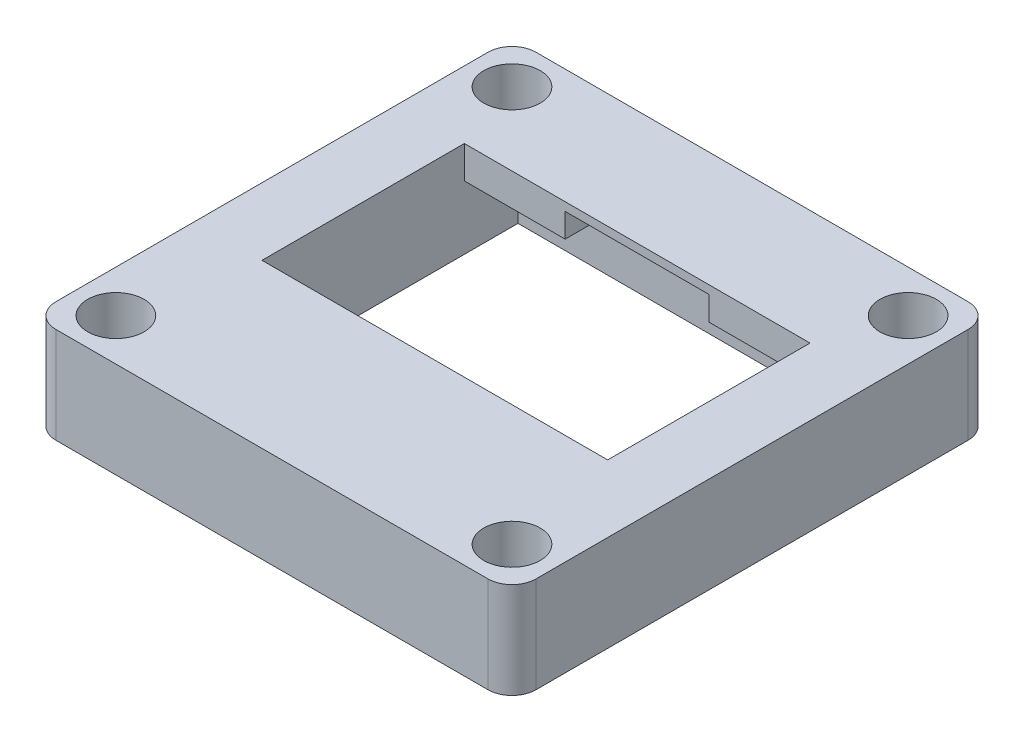
SolidWorks part; units mm, degrees
ref_plane "Спереди" through (0, 0, 0) normal (0, 0, 1) x (1, 0, 0)
ref_plane "Сверху" through (0, 0, 0) normal (0, 1, 0) x (1, 0, 0)
ref_plane "Справа" through (0, 0, 0) normal (1, 0, 0) x (0, 0, -1)
sketch "габариты дисплея" plane through (0, 0, 0) normal (0, 1, 0) x (1, 0, 0)
  line L1 (-13.6, -13.6) -> (13.6, -13.6)
  line L2 (-13.6, -13.6) -> (-13.6, 13.6)
  line L3 (-13.6, 13.6) -> (13.6, 13.6)
  line L4 (13.6, -13.6) -> (13.6, 13.6)
  line L5 (-13.6, -13.6) -> (13.6, 13.6) construction
  line L6 (-13.6, 13.6) -> (13.6, -13.6) construction
  line L7 (-13.6, -9.63) -> (13.6, -9.63)
  line L8 (-13.6, -9.63) -> (-13.6, 9.63)
  line L9 (-13.6, 9.63) -> (13.6, 9.63)
  line L10 (13.6, -9.63) -> (13.6, 9.63)
  line L11 (-13.6, -9.63) -> (13.6, 9.63) construction
  line L12 (-13.6, 9.63) -> (13.6, -9.63) construction
  line L13 (-11.6, -11.6) -> (11.6, -11.6) construction
  line L14 (-11.6, -11.6) -> (-11.6, 11.6) construction
  line L15 (-11.6, 11.6) -> (11.6, 11.6) construction
  line L16 (11.6, -11.6) -> (11.6, 11.6) construction
  line L17 (-11.6, -11.6) -> (11.6, 11.6) construction
  line L18 (-11.6, 11.6) -> (11.6, -11.6) construction
  circle A0 centre (-11.6, 11.6) radius 1.25
  circle A1 centre (11.6, 11.6) radius 1.25
  circle A2 centre (11.6, -11.6) radius 1.25
  circle A3 centre (-11.6, -11.6) radius 1.25
  point P0 (0, 0)
  point P6 (0, 0)
  point P12 (0, 0)
  dimension "D5" = 2.5
  dimension "D1" = 19.26
  dimension "D2" = 27.2
  dimension "D3" = 27.2
  dimension "D4" = 2
sketch "Эскиз1" plane through (0, 0, 0) normal (0, 1, 0) x (1, 0, 0)
  line L1 (-20, 20) -> (20, 20)
  line L2 (-20, 20) -> (-20, -20)
  line L3 (-20, -20) -> (20, -20)
  line L4 (20, 20) -> (20, -20)
  line L5 (-20, 20) -> (20, -20) construction
  line L6 (-20, -20) -> (20, 20) construction
  point P0 (0, 0)
  dimension "D1" = 40
  dimension "D2" = 40
extrude "тело" add sketch "Эскиз1" along normal blind 8
sketch "Эскиз2" plane through (0, 0, 0) normal (0, -1, 0) x (1, 0, 0)
  line L0 (-13.6, 13.6) -> (13.6, 13.6) construction
  line L1 (-14.4, -14.9) -> (14.4, -14.9)
  line L2 (-14.4, -14.9) -> (-14.4, 14.9)
  line L3 (-14.4, 14.9) -> (14.4, 14.9)
  line L4 (14.4, -14.9) -> (14.4, 14.9)
  line L5 (-14.4, -14.9) -> (14.4, 14.9) construction
  line L6 (-14.4, 14.9) -> (14.4, -14.9) construction
  line L7 (13.6, 13.6) -> (13.6, -13.6) construction
  point P0 (0, 0)
  dimension "D1" = 1.3
  dimension "D2" = 0.8
extrude "углубление для платы" cut sketch "Эскиз2" against normal offset from surface (5.3 mm away) 2.7 up to face at (0, 8, 0)
sketch "Эскиз3" plane through (0, 5.3, 0) normal (0, -1, 0) x (1, 0, 0)
  line L0 (14.4, -14.9) -> (14.4, 14.9) construction
  line L1 (-14.4, -10.43) -> (14.4, -10.43)
  line L2 (-14.4, -10.43) -> (-14.4, 10.43)
  line L3 (-14.4, 10.43) -> (14.4, 10.43)
  line L4 (14.4, -10.43) -> (14.4, 10.43)
  line L5 (-14.4, -10.43) -> (14.4, 10.43) construction
  line L6 (-14.4, 10.43) -> (14.4, -10.43) construction
  line L7 (-13.6, 9.63) -> (13.6, 9.63) construction
  point P0 (0, 0)
  dimension "D1" = 0.8
extrude "отверстие для дисплея" cut sketch "Эскиз3" against normal through all
sketch "Эскиз4" plane through (0, 5.3, 0) normal (0, -1, 0) x (1, 0, 0)
  line L0 (14.4, 10.43) -> (-14.4, 10.43) construction
  line L1 (-6, 10.43) -> (6, 10.43)
  line L2 (-6, 10.43) -> (-6, 14.9)
  line L3 (-6, 14.9) -> (6, 14.9)
  line L4 (6, 10.43) -> (6, 14.9)
  line L5 (14.4, 14.9) -> (-14.4, 14.9) construction
  line L6 (-14.4, -10.43) -> (14.4, -10.43) construction
  line L7 (6, -10.43) -> (-6, -10.43)
  line L8 (6, -10.43) -> (6, -14.9)
  line L9 (6, -14.9) -> (-6, -14.9)
  line L10 (-6, -10.43) -> (-6, -14.9)
  line L11 (-14.4, -14.9) -> (14.4, -14.9) construction
  point P16 (0, -10.43)
  point P18 (0, 10.43)
  dimension "D1" = 12
extrude "углубление для шлейфа и пинов" cut sketch "Эскиз4" against normal offset from surface (2 mm away) 0.7 up to face at (0, 8, 0)
sketch "Эскиз5" plane through (0, 0, 10.43) normal (0, 0, -1) x (-1, 0, 0)
  line L1 (-14.4, 8) -> (-14.4, 5.3) construction
  line L2 (14.4, 8) -> (-14.4, 8)
  line L3 (14.4, 8) -> (14.4, 7.5)
  line L4 (14.4, 7.5) -> (-14.4, 7.5)
  line L6 (-14.4, 8) -> (-14.4, 7.5)
  dimension "D1" = 0.5
extrude "щит нижней части дисплея" add sketch "Эскиз5" along normal blind 4
sketch "Эскиз7" plane through (0, 0, 0) normal (0, -1, 0) x (1, 0, 0)
  line L1 (-16.5, -16.5) -> (16.5, -16.5) construction
  line L2 (-16.5, -16.5) -> (-16.5, 16.5) construction
  line L3 (-16.5, 16.5) -> (16.5, 16.5) construction
  line L4 (16.5, -16.5) -> (16.5, 16.5) construction
  line L5 (-16.5, -16.5) -> (16.5, 16.5) construction
  line L6 (-16.5, 16.5) -> (16.5, -16.5) construction
  circle A0 centre (-16.5, 16.5) radius 1.25
  circle A1 centre (16.5, 16.5) radius 1.25
  circle A2 centre (16.5, -16.5) radius 1.25
  circle A3 centre (-16.5, -16.5) radius 1.25
  point P0 (0, 0)
  dimension "D3" = 2.5
  dimension "D1" = 33
  dimension "D2" = 33
extrude "крепежные отверстия" cut sketch "Эскиз7" against normal through all
fillet "Скругление1" radius 2 4 edges at (-20, 4, -20) (20, 4, -20) (20, 4, 20) (-20, 4, 20)
sketch "Эскиз8" plane through (0, 8, 0) normal (0, 1, 0) x (1, 0, 0)
  circle A0 centre (-16.5, 16.5) radius 2.35
  circle A1 centre (-16.5, -16.5) radius 2.35
  circle A2 centre (16.5, -16.5) radius 2.35
  circle A3 centre (16.5, 16.5) radius 2.35
  dimension "D1" = 4.7
extrude "Углубления под шляпки" cut sketch "Эскиз8" against normal blind 4
